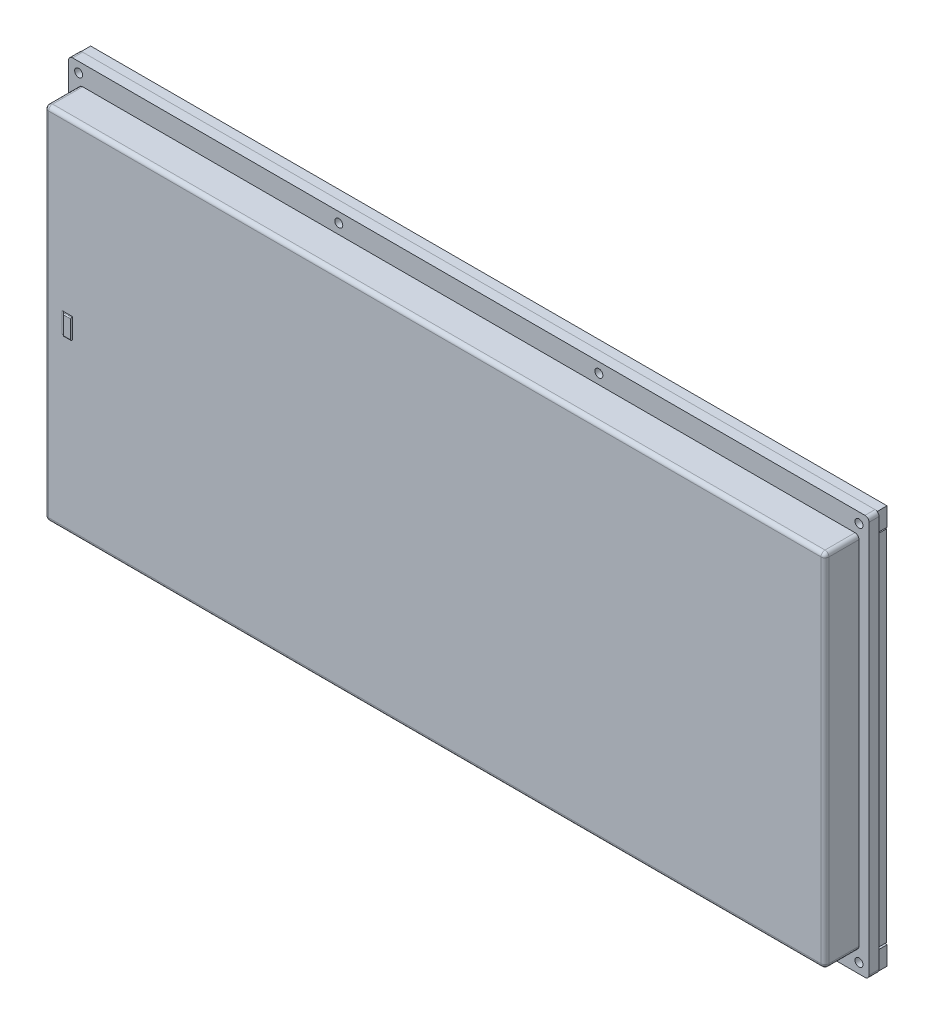
SolidWorks part; units mm, degrees
ref_plane "Ön Düzlem" through (0, 0, 0) normal (0, 0, 1) x (1, 0, 0)
ref_plane "Üst Düzlem" through (0, 0, 0) normal (0, 1, 0) x (1, 0, 0)
ref_plane "Sağ Düzlem" through (0, 0, 0) normal (1, 0, 0) x (0, 0, -1)
sketch "Çizim1" plane through (0, 0, 0) normal (0, 0, 1) x (1, 0, 0)
  line L0 (-195, 90) -> (-195, 100) construction
  line L1 (-198, -100) -> (198, -100)
  line L2 (-200, -98) -> (-200, 98)
  line L3 (-198, 100) -> (198, 100)
  line L4 (200, -98) -> (200, 98)
  line L5 (-200, -100) -> (200, 100) construction
  line L6 (-200, 100) -> (200, -100) construction
  line L11 (-150.7289, -75.3644) -> (150.7289, 75.3644) construction
  line L12 (-150.7289, 75.3644) -> (150.7289, -75.3644) construction
  line L17 (-192.5437, -96.9685) -> (194.9146, 98.1625) construction
  line L18 (-195, 90) -> (198.8912, -91.7959) construction
  line L19 (-90.9499, 0) -> (126.8653, 0) construction
  circle A0 centre (-195, 95) radius 2
  circle A1 centre (-65, 95) radius 2
  circle A2 centre (65, 95) radius 2
  circle A3 centre (195, 95) radius 2
  circle A4 centre (195, -95) radius 2
  circle A5 centre (65, -95) radius 2
  circle A6 centre (-65, -95) radius 2
  circle A7 centre (-195, -95) radius 2
  arc A8 (-200, 98) -> (-198, 100) centre (-198, 98) cw
  arc A9 (200, 98) -> (198, 100) centre (198, 98) ccw
  arc A10 (200, -98) -> (198, -100) centre (198, -98) cw
  arc A11 (-198, -100) -> (-200, -98) centre (-198, -98) cw
  point P0 (0, 0)
  point P5 (0, 0)
  point P11 (0, 0)
  dimension "D5" = 4
  dimension "D10" = 190
  dimension "D11" = 2
  dimension "D12" = 2
  dimension "D1" = 200
  dimension "D2" = 400
  dimension "D3" = 190
  dimension "D4" = 390
  dimension "D7" = 130
  dimension "D8" = 5
  dimension "D9" = 5
  dimension "D6" = 4
extrude "Yükseklik-Ekstrüzyon1" add sketch "Çizim1" along normal blind 5
sketch "Çizim3" plane through (0, 0, 5) normal (0, 0, 1) x (1, 0, 0)
  line L0 (-200, 98) -> (-200, -98) construction
  line L1 (198, 100) -> (-198, 100) construction
  line L2 (-200, 98) -> (-200, -98)
  line L3 (198, 100) -> (-198, 100)
  line L5 (195, -90) -> (-195, -90)
  line L6 (195, -90) -> (195, 90)
  line L7 (195, 90) -> (-195, 90)
  line L8 (-195, -90) -> (-195, 90)
  line L9 (195, -90) -> (-195, 90) construction
  line L10 (195, 90) -> (-195, -90) construction
  circle A0 centre (-195, 95) radius 2 construction
  circle A1 centre (-195, 95) radius 2
  point P7 (0, 0)
  dimension "D1" = 5
  dimension "D2" = 5
extrude "Yükseklik-Ekstrüzyon2" add sketch "Çizim3" along normal blind 17 separate body contours L7 L8 L5 L6
fillet "Radyus1" radius 2 8 edges at (0, -90, 22) (-195, 0, 22) (0, 90, 22) (195, 0, 22) (-195, -90, 13.5) (-195, 90, 13.5) (195, -90, 13.5) (195, 90, 13.5)
sketch "Çizim7" plane through (0, 0, 0) normal (0, 1, 0) x (1, 0, 0)
  line L0 (193, -22) -> (-193, -22) construction
  line L1 (-184.5, -23) -> (-181, -23)
  line L2 (-181, -23) -> (-181, -22)
  line L3 (-193, -5) -> (-193, -20) construction
  line L4 (-186.4439, -22) -> (-181, -22)
  arc A0 (-186.4439, -22) -> (-184.5, -23) centre (-186.4439, -24.3894) cw
  dimension "D1" = 1
  dimension "D4" = 2.3894
  dimension "D2" = 3.5
  dimension "D3" = 12
extrude "Yükseklik-Ekstrüzyon3" add sketch "Çizim7" along normal mid plane 10
fillet "Radyus2" radius 0.5 2 edges at (-182.75, -5, 23) (-182.75, 5, 23)
sketch "Çizim8" plane through (0, 0, 0) normal (0, 0, 1) x (1, 0, 0)
  line L8 (0, -90.35) -> (0, -99.65) construction
  line L9 (-199, -99.65) -> (199, -99.65)
  line L10 (-199, -99.65) -> (-199, -90.35)
  line L11 (-199, -90.35) -> (199, -90.35)
  line L12 (199, -99.65) -> (199, -90.35)
  circle A1 centre (-195, -95) radius 2 construction
  circle A2 centre (-195, -95) radius 2
  circle A3 centre (195, -95) radius 2.7
  circle A4 centre (65, -95) radius 2.7
  circle A5 centre (-65, -95) radius 2.7
  circle A6 centre (-195, -95) radius 2.7
  circle A7 centre (65, -95) radius 2 construction
  circle A9 centre (-65, -95) radius 2 construction
  point P0 (0, 0)
  point P17 (0, -95)
  dimension "D5" = 5.4
  dimension "D3" = 398
  dimension "D4" = 9.3
extrude "Yükseklik-Ekstrüzyon4" add sketch "Çizim8" against normal blind 5 separate body contours L11 L8 L9 L10 A6 A5 | L8 L11 L12 L9 A3 A4
mirror "Aynalama1" about plane through (0, 0, 0) normal (0, 1, 0) of "Yükseklik-Ekstrüzyon4"
sketch "Çizim9" plane through (0, 0, 0) normal (0, 0, -1) x (-1, 0, 0)
  line L0 (-199, 99.65) -> (-199, 90.35) construction
  line L1 (199, 90.35) -> (-199, 90.35) construction
  line L2 (199, 99.65) -> (-199, 99.65) construction
  line L3 (-200, -98) -> (-200, 98) construction
  line L4 (-199, 99.65) -> (-199, 90.35)
  line L5 (199, 90.35) -> (-199, 90.35)
  line L6 (199, 99.65) -> (-199, 99.65)
  line L7 (-200, -98) -> (-200, 98)
  line L9 (-198.75, 89.55) -> (-191.25, 89.55)
  line L10 (-198.75, 89.55) -> (-198.75, -89.55)
  line L11 (-198.75, -89.55) -> (-191.25, -89.55)
  line L12 (-191.25, 89.55) -> (-191.25, -89.55)
  circle A0 centre (-195, 95) radius 2.7 construction
  circle A1 centre (-195, 95) radius 2 construction
  circle A2 centre (-195, 95) radius 2.7
  circle A3 centre (-195, 95) radius 2
  circle A4 centre (-195, -95) radius 2.7 construction
  circle A5 centre (-195, -95) radius 2 construction
  circle A6 centre (-195, -95) radius 2.7
  circle A7 centre (-195, -95) radius 2
  point P23 (-195, -89.55)
  dimension "D1" = 5.45
  dimension "D2" = 179.1
  dimension "D3" = 7.5
extrude "Yükseklik-Ekstrüzyon5" add sketch "Çizim9" along normal blind 5 contours L12 L11 L10 L9
mirror "Aynalama2" about plane through (0, 0, 0) normal (1, 0, 0) of "Yükseklik-Ekstrüzyon5"
sketch "Çizim10" plane through (0, 0, 0) normal (0, 0, -1) x (-1, 0, 0)
  line L0 (199, -90.35) -> (-199, -90.35) construction
  line L1 (-191.25, 89.55) -> (-191.25, -89.55) construction
  line L2 (199, -90.35) -> (-199, -90.35)
  line L3 (-191.25, 89.55) -> (-191.25, -89.55)
  line L4 (198, 100) -> (-198, 100)
  line L5 (-200, 98) -> (-200, -98)
  line L6 (-198, -100) -> (198, -100)
  line L7 (200, -98) -> (200, 98)
  line L8 (198, 100) -> (-198, 100)
  line L9 (-200, 98) -> (-200, -98)
  line L10 (-198, -100) -> (198, -100)
  line L11 (200, -98) -> (200, 98)
  line L12 (15.4, 0) -> (-15.4, 0) construction
  circle A0 centre (-187.31, -82.76) radius 2
  circle A1 centre (-65.81, -82.76) radius 2
  circle A2 centre (55.69, -82.76) radius 2
  circle A3 centre (177.19, -82.76) radius 2
  arc A4 (200, 98) -> (198, 100) centre (198, 98) ccw
  arc A5 (-198, 100) -> (-200, 98) centre (-198, 98) ccw
  arc A6 (-200, -98) -> (-198, -100) centre (-198, -98) ccw
  arc A7 (198, -100) -> (200, -98) centre (198, -98) ccw
  arc A8 (200, 98) -> (198, 100) centre (198, 98) ccw
  arc A9 (-198, 100) -> (-200, 98) centre (-198, 98) ccw
  arc A10 (-200, -98) -> (-198, -100) centre (-198, -98) ccw
  arc A11 (198, -100) -> (200, -98) centre (198, -98) ccw
  circle A12 centre (177.19, 82.76) radius 2
  circle A13 centre (55.69, 82.76) radius 2
  circle A14 centre (-65.81, 82.76) radius 2
  circle A15 centre (-187.31, 82.76) radius 2
  dimension "D2" = 3.94
  dimension "D3" = 4
  dimension "D1" = 0
  dimension "D5" = 4
extrude "Kes-Ekstrüzyon1" cut sketch "Çizim10" against normal up to next (5 mm away) contours A15 | A14 | A13 | A12 | A3 | A2 | A1 | A0
sketch "Çizim12" plane through (0, 0, 0) normal (0, 0, -1) x (-1, 0, 0)
  line L0 (199, -90.35) -> (-199, -90.35) construction
  line L1 (-199, -90.35) -> (-199, -99.65) construction
  line L2 (-199, -99.65) -> (199, -99.65) construction
  line L3 (199, -99.65) -> (199, -90.35) construction
  line L4 (198.75, 89.55) -> (191.25, 89.55) construction
  line L5 (191.25, 89.55) -> (191.25, -89.55) construction
  line L6 (191.25, -89.55) -> (198.75, -89.55) construction
  line L7 (198.75, -89.55) -> (198.75, 89.55) construction
  line L8 (198, 100) -> (-198, 100) construction
  line L9 (-200, 98) -> (-200, -98) construction
  line L10 (-198, -100) -> (198, -100) construction
  line L11 (200, -98) -> (200, 98) construction
  line L12 (-191.25, 89.55) -> (-198.75, 89.55) construction
  line L13 (-198.75, 89.55) -> (-198.75, -89.55) construction
  line L14 (-198.75, -89.55) -> (-191.25, -89.55) construction
  line L15 (-191.25, -89.55) -> (-191.25, 89.55) construction
  line L16 (-199, 90.35) -> (199, 90.35) construction
  line L17 (199, 90.35) -> (199, 99.65) construction
  line L18 (199, 99.65) -> (-199, 99.65) construction
  line L19 (-199, 99.65) -> (-199, 90.35) construction
  line L20 (199, -90.35) -> (-199, -90.35)
  line L21 (-199, -90.35) -> (-199, -99.65)
  line L22 (-199, -99.65) -> (199, -99.65)
  line L23 (199, -99.65) -> (199, -90.35)
  line L24 (198.75, 89.55) -> (191.25, 89.55)
  line L25 (191.25, 89.55) -> (191.25, -89.55)
  line L26 (191.25, -89.55) -> (198.75, -89.55)
  line L27 (198.75, -89.55) -> (198.75, 89.55)
  line L28 (198, 100) -> (-198, 100)
  line L29 (-200, 98) -> (-200, -98)
  line L30 (-198, -100) -> (198, -100)
  line L31 (200, -98) -> (200, 98)
  line L32 (-191.25, 89.55) -> (-198.75, 89.55)
  line L33 (-198.75, 89.55) -> (-198.75, -89.55)
  line L34 (-198.75, -89.55) -> (-191.25, -89.55)
  line L35 (-191.25, -89.55) -> (-191.25, 89.55)
  line L36 (-199, 90.35) -> (199, 90.35)
  line L37 (199, 90.35) -> (199, 99.65)
  line L38 (199, 99.65) -> (-199, 99.65)
  line L39 (-199, 99.65) -> (-199, 90.35)
  line L40 (-176.25, 89.76) -> (44.63, 89.76)
  line L41 (44.63, -89.76) -> (-58.81, -89.76)
  line L42 (-178.25, 87.76) -> (-178.25, 86.1785)
  line L43 (-182.25, 82.1785) -> (-182.75, 82.1785)
  line L44 (-183.75, 81.1785) -> (-183.75, -81.1785)
  line L45 (15.4, 0) -> (-15.4, 0) construction
  line L46 (-178.25, -87.76) -> (-178.25, -86.1785)
  line L47 (-182.25, -82.1785) -> (-182.75, -82.1785)
  line L48 (-176.25, -89.76) -> (-72.81, -89.76)
  line L49 (-70.81, -82.76) -> (-70.81, -87.76)
  line L50 (-65.81, -77.8371) -> (-65.81, -45.8559) construction
  line L51 (46.63, -87.76) -> (46.63, -86.1785)
  line L52 (50.63, -82.1785) -> (51.13, -82.1785)
  line L53 (52.13, 81.1785) -> (52.13, -81.1785)
  line L54 (50.63, 82.1785) -> (51.13, 82.1785)
  line L55 (46.63, 87.76) -> (46.63, 86.1785)
  line L56 (-60.81, -82.76) -> (-60.81, -87.76)
  line L57 (55.13, 76.6283) -> (55.13, 65.3958) construction
  line L58 (63.63, -87.76) -> (63.63, -86.1785)
  line L59 (59.63, -82.1785) -> (59.13, -82.1785)
  line L60 (58.13, 81.1785) -> (58.13, -81.1785)
  line L61 (59.63, 82.1785) -> (59.13, 82.1785)
  line L62 (63.63, 87.76) -> (63.63, 86.1785)
  line L63 (65.63, 89.76) -> (166.63, 89.76)
  line L64 (116.13, 89.76) -> (116.13, 92.3963) construction
  line L65 (168.63, -87.76) -> (168.63, -86.1785)
  line L66 (172.63, -82.1785) -> (173.13, -82.1785)
  line L67 (174.13, 81.1785) -> (174.13, -81.1785)
  line L68 (172.63, 82.1785) -> (173.13, 82.1785)
  line L69 (168.63, 87.76) -> (168.63, 86.1785)
  line L70 (65.63, -89.76) -> (166.63, -89.76)
  arc A0 (200, 98) -> (198, 100) centre (198, 98) ccw construction
  arc A1 (-198, 100) -> (-200, 98) centre (-198, 98) ccw construction
  arc A2 (-200, -98) -> (-198, -100) centre (-198, -98) ccw construction
  arc A3 (198, -100) -> (200, -98) centre (198, -98) ccw construction
  arc A4 (200, 98) -> (198, 100) centre (198, 98) ccw
  arc A5 (-198, 100) -> (-200, 98) centre (-198, 98) ccw
  arc A6 (-200, -98) -> (-198, -100) centre (-198, -98) ccw
  arc A7 (198, -100) -> (200, -98) centre (198, -98) ccw
  arc A8 (-176.25, 89.76) -> (-178.25, 87.76) centre (-176.25, 87.76) ccw
  arc A9 (-182.75, 82.1785) -> (-183.75, 81.1785) centre (-182.75, 81.1785) ccw
  arc A10 (-178.25, 86.1785) -> (-182.25, 82.1785) centre (-182.25, 86.1785) cw
  arc A11 (-176.25, -89.76) -> (-178.25, -87.76) centre (-176.25, -87.76) cw
  arc A12 (-178.25, -86.1785) -> (-182.25, -82.1785) centre (-182.25, -86.1785) ccw
  arc A13 (-182.75, -82.1785) -> (-183.75, -81.1785) centre (-182.75, -81.1785) cw
  arc A14 (44.63, -89.76) -> (46.63, -87.76) centre (44.63, -87.76) ccw
  circle A15 centre (-65.81, -82.76) radius 2 construction
  circle A16 centre (-65.81, -82.76) radius 2
  arc A17 (-65.81, -77.76) -> (-70.81, -82.76) centre (-65.81, -82.76) ccw
  arc A18 (-70.81, -87.76) -> (-72.81, -89.76) centre (-72.81, -87.76) cw
  arc A19 (46.63, -86.1785) -> (50.63, -82.1785) centre (50.63, -86.1785) cw
  circle A20 centre (177.19, -82.76) radius 2 construction
  circle A21 centre (55.69, -82.76) radius 2 construction
  circle A22 centre (177.19, -82.76) radius 2
  circle A23 centre (55.69, -82.76) radius 2
  arc A24 (51.13, -82.1785) -> (52.13, -81.1785) centre (51.13, -81.1785) ccw
  arc A25 (51.13, 82.1785) -> (52.13, 81.1785) centre (51.13, 81.1785) cw
  arc A26 (44.63, 89.76) -> (46.63, 87.76) centre (44.63, 87.76) cw
  arc A27 (46.63, 86.1785) -> (50.63, 82.1785) centre (50.63, 86.1785) ccw
  arc A28 (-60.81, -87.76) -> (-58.81, -89.76) centre (-58.81, -87.76) ccw
  arc A29 (-65.81, -77.76) -> (-60.81, -82.76) centre (-65.81, -82.76) cw
  arc A30 (65.63, -89.76) -> (63.63, -87.76) centre (65.63, -87.76) cw
  arc A31 (63.63, -86.1785) -> (59.63, -82.1785) centre (59.63, -86.1785) ccw
  arc A32 (59.13, -82.1785) -> (58.13, -81.1785) centre (59.13, -81.1785) cw
  arc A33 (59.13, 82.1785) -> (58.13, 81.1785) centre (59.13, 81.1785) ccw
  arc A34 (65.63, 89.76) -> (63.63, 87.76) centre (65.63, 87.76) ccw
  arc A35 (63.63, 86.1785) -> (59.63, 82.1785) centre (59.63, 86.1785) cw
  arc A36 (166.63, -89.76) -> (168.63, -87.76) centre (166.63, -87.76) ccw
  arc A37 (168.63, -86.1785) -> (172.63, -82.1785) centre (172.63, -86.1785) cw
  arc A38 (173.13, -82.1785) -> (174.13, -81.1785) centre (173.13, -81.1785) ccw
  arc A39 (173.13, 82.1785) -> (174.13, 81.1785) centre (173.13, 81.1785) cw
  arc A40 (168.63, 86.1785) -> (172.63, 82.1785) centre (172.63, 86.1785) ccw
  arc A41 (166.63, 89.76) -> (168.63, 87.76) centre (166.63, 87.76) cw
  point P34 (-69.3455, -79.2245)
  point P55 (-183.75, 0)
  point P79 (-65.81, 89.76)
  point P129 (116.13, 92.3963)
  dimension "D2" = 2
  dimension "D3" = 1
  dimension "D4" = 4
  dimension "D8" = 10
  dimension "D9" = 2
  dimension "D10" = 3
  dimension "D1" = 0.59
  dimension "D5" = 7.5
  dimension "D6" = 1.5815
  dimension "D7" = 7.5
  dimension "D11" = 58
extrude "Yükseklik-Ekstrüzyon7" add sketch "Çizim12" along normal blind 2 separate body contours A28 L41 A14 L51 A19 L52 A24 L53 A25 L54 A27 L55 A26 L40 A8 L42 A10 L43 A9 L44 A13 L47 A12 L46 A11 L48 A18 L49 A17 A29 L56 | L70 A36 L65 A37 L66 A38 L67 A39 L68 A40 L69 A41 L63 A34 L62 A35 L61 A33 L60 A32 L59 A31 L58 A30
sketch "Çizim13" plane through (0, 0, -2) normal (0, 0, -1) x (-1, 0, 0)
  line L0 (-168.75, 86.76) -> (-168.75, 59.24)
  line L1 (-176.25, 89.76) -> (44.63, 89.76) construction
  line L2 (-171.75, 56.24) -> (-180.75, 56.24)
  line L3 (-183.75, 81.1785) -> (-183.75, -81.1785) construction
  line L4 (-183.75, 53.24) -> (-183.75, -65.76)
  line L7 (-91.75, -76.76) -> (-27.75, -76.76)
  line L9 (-24.75, -79.76) -> (-24.75, -86.76)
  line L12 (199, -90.35) -> (-199, -90.35) construction
  line L13 (-165.75, 89.76) -> (34.13, 89.76)
  line L14 (37.13, 86.76) -> (37.13, 59.24)
  line L20 (-180.75, -68.76) -> (-168.75, -68.76)
  line L21 (-168.75, -68.76) -> (-168.75, -73.76)
  line L22 (-165.75, -76.76) -> (-108.75, -76.76)
  line L23 (-105.75, -79.76) -> (-105.75, -86.76)
  line L24 (-176.25, -89.76) -> (-72.81, -89.76) construction
  line L25 (-102.75, -89.76) -> (-97.75, -89.76)
  line L26 (-94.75, -86.76) -> (-94.75, -79.76)
  line L28 (44.63, -89.76) -> (-58.81, -89.76) construction
  line L29 (-21.75, -89.76) -> (-16.75, -89.76)
  line L30 (-13.75, -86.76) -> (-13.75, -79.76)
  line L31 (-10.75, -76.76) -> (34.13, -76.76)
  line L32 (-168.75, -68.76) -> (-168.75, 56.24)
  line L33 (37.13, -71.76) -> (37.13, -73.76)
  line L34 (52.13, 81.1785) -> (52.13, -81.1785) construction
  line L37 (40.13, -68.76) -> (49.13, -68.76)
  line L38 (52.13, -65.76) -> (52.13, 53.24)
  line L39 (49.13, 56.24) -> (40.13, 56.24)
  line L40 (37.13, 56.24) -> (37.13, -68.76)
  arc A0 (-180.75, 56.24) -> (-183.75, 53.24) centre (-180.75, 53.24) ccw
  arc A1 (-168.75, 86.76) -> (-165.75, 89.76) centre (-165.75, 86.76) cw
  arc A4 (-183.75, -65.76) -> (-180.75, -68.76) centre (-180.75, -65.76) ccw
  arc A5 (-168.75, -73.76) -> (-165.75, -76.76) centre (-165.75, -73.76) ccw
  arc A6 (-108.75, -76.76) -> (-105.75, -79.76) centre (-108.75, -79.76) cw
  arc A7 (-105.75, -86.76) -> (-102.75, -89.76) centre (-102.75, -86.76) ccw
  arc A8 (-97.75, -89.76) -> (-94.75, -86.76) centre (-97.75, -86.76) ccw
  arc A9 (-94.75, -79.76) -> (-91.75, -76.76) centre (-91.75, -79.76) cw
  arc A10 (-27.75, -76.76) -> (-24.75, -79.76) centre (-27.75, -79.76) cw
  arc A11 (-24.75, -86.76) -> (-21.75, -89.76) centre (-21.75, -86.76) ccw
  arc A12 (-16.75, -89.76) -> (-13.75, -86.76) centre (-16.75, -86.76) ccw
  arc A13 (-13.75, -79.76) -> (-10.75, -76.76) centre (-10.75, -79.76) cw
  arc A14 (34.13, -76.76) -> (37.13, -73.76) centre (34.13, -73.76) ccw
  arc A15 (40.13, -68.76) -> (37.13, -71.76) centre (40.13, -71.76) ccw
  arc A16 (-168.75, 59.24) -> (-171.75, 56.24) centre (-171.75, 59.24) cw
  arc A17 (49.13, -68.76) -> (52.13, -65.76) centre (49.13, -65.76) ccw
  arc A18 (34.13, 89.76) -> (37.13, 86.76) centre (34.13, 86.76) cw
  arc A19 (40.13, 56.24) -> (37.13, 59.24) centre (40.13, 59.24) cw
  arc A20 (52.13, 53.24) -> (49.13, 56.24) centre (49.13, 53.24) ccw
  point P13 (-168.75, -68.76)
  point P23 (37.13, 70.4165)
  point P25 (-183.75, 56.24)
  point P28 (-168.75, 89.76)
  point P37 (-183.75, -68.76)
  point P40 (-168.75, -76.76)
  point P48 (-105.75, -76.76)
  point P52 (-105.75, -89.76)
  point P55 (-94.75, -89.76)
  point P58 (-94.75, -76.76)
  point P61 (-24.75, -76.76)
  point P64 (-24.75, -89.76)
  point P67 (-13.75, -89.76)
  point P75 (37.13, 55.2307)
  point P80 (52.13, -68.76)
  point P83 (37.13, 89.76)
  point P89 (52.13, 56.24)
  dimension "D3" = 3
  dimension "D4" = 125
  dimension "D7" = 3
  dimension "D8" = 3
  dimension "D16" = 3
  dimension "D2" = 15
  dimension "D5" = 8
  dimension "D6" = 15
  dimension "D9" = 60
  dimension "D10" = 13
  dimension "D11" = 11
  dimension "D12" = 11
  dimension "D13" = 70
  dimension "D14" = 125
  dimension "D15" = 21.59
